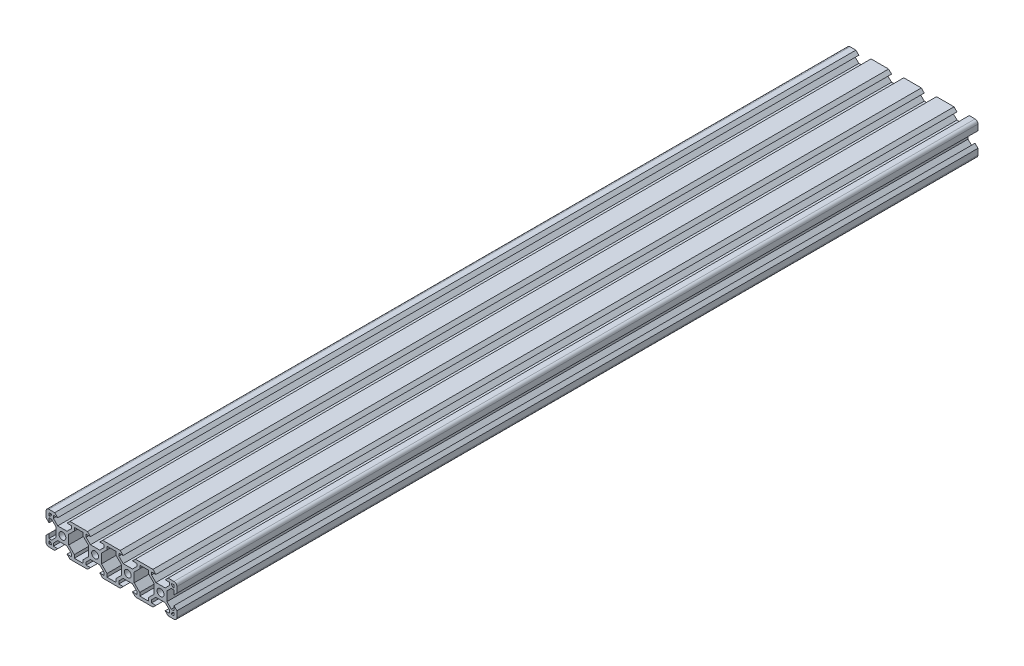
SolidWorks part; units mm, degrees
material "6063-T5"
ref_plane "Plane1" through (0, 0, 0) normal (0, 0, 1) x (1, 0, 0)
ref_plane "Plane2" through (0, 0, 0) normal (0, 1, 0) x (1, 0, 0)
ref_plane "Plane3" through (0, 0, 0) normal (1, 0, 0) x (0, 0, -1)
sketch "Sketch1" plane through (0, 0, 0) normal (0, 0, 1) x (1, 0, 0)
  line L0 (0, 0) -> (0, 10) construction
  line L1 (0, 0) -> (-40, 0) construction
  line L2 (-40, 10) -> (-30, 0) construction
  line L3 (-30, 0) -> (-20, 10) construction
  line L4 (-20, 10) -> (-10, 0) construction
  line L5 (-10, 0) -> (0, 10) construction
  line L6 (-10, 0) -> (-10, 10) construction
  line L7 (-20, 10) -> (-20, 0) construction
  line L8 (-40, 0) -> (-40, 10) construction
  line L9 (-38.2, 10) -> (-34.64, 10)
  line L10 (-34.64, 10) -> (-32.84, 8.2)
  line L11 (-32.84, 8.2) -> (-35.4993, 8.2)
  line L12 (-35.4993, 8.2) -> (-35.4993, 6.56)
  line L13 (-35.4993, 6.56) -> (-32.84, 3.9007)
  line L14 (-32.84, 3.9007) -> (-27.16, 3.9007)
  line L15 (-30, 0) -> (-30, 10) construction
  line L16 (-33.9007, 2.84) -> (-33.9007, 0)
  line L17 (-36.56, 5.4993) -> (-33.9007, 2.84)
  line L18 (-38.2, 5.4993) -> (-36.56, 5.4993)
  line L19 (-38.2, 2.84) -> (-38.2, 5.4993)
  line L20 (-40, 4.64) -> (-38.2, 2.84)
  line L21 (-40, 8.2) -> (-40, 4.64)
  line L22 (-38.2, 8.2) -> (-38.2, 6.5693)
  line L23 (-38.2, 6.5693) -> (-37.63, 6.5693)
  line L24 (-37.63, 6.5693) -> (-36.5693, 7.63)
  line L25 (-36.5693, 7.63) -> (-36.5693, 8.2)
  line L26 (-36.5693, 8.2) -> (-38.2, 8.2)
  line L27 (-17.3, 6.2393) -> (-17.3, 8.2)
  line L28 (-13.9007, 2.84) -> (-17.3, 6.2393)
  line L29 (-13.9007, -2.84) -> (-13.9007, 2.84)
  line L30 (-14.64, 10) -> (-12.84, 8.2)
  line L31 (-12.84, 8.2) -> (-15.4993, 8.2)
  line L32 (-15.4993, 8.2) -> (-15.4993, 6.56)
  line L33 (-15.4993, 6.56) -> (-12.84, 3.9007)
  line L34 (-12.84, 3.9007) -> (-7.16, 3.9007)
  line L35 (-5.36, 10) -> (-7.16, 8.2)
  line L36 (-7.16, 8.2) -> (-4.5007, 8.2)
  line L37 (-4.5007, 8.2) -> (-4.5007, 6.56)
  line L38 (-4.5007, 6.56) -> (-7.16, 3.9007)
  line L39 (-5.36, 10) -> (5.36, 10)
  line L40 (-6.0993, -2.84) -> (-6.0993, 2.84)
  line L41 (-6.0993, 2.84) -> (-2.7, 6.2393)
  line L42 (-2.7, 6.2393) -> (-2.7, 8.2)
  line L43 (-2.7, 8.2) -> (2.7, 8.2)
  line L44 (-25.36, 10) -> (-27.16, 8.2)
  line L45 (-7.16, 3.9007) -> (-6.0993, 2.84) construction
  line L46 (-36.5693, -7.63) -> (-36.5693, -8.2)
  line L47 (-37.63, -6.5693) -> (-36.5693, -7.63)
  line L48 (-38.2, -6.5693) -> (-37.63, -6.5693)
  line L49 (-38.2, -8.2) -> (-38.2, -6.5693)
  line L50 (-27.16, 8.2) -> (-24.5007, 8.2)
  line L51 (-24.5007, 8.2) -> (-24.5007, 6.56)
  line L52 (-24.5007, 6.56) -> (-27.16, 3.9007)
  line L53 (-25.36, 10) -> (-14.64, 10)
  line L54 (-26.0993, -2.84) -> (-26.0993, 2.84)
  line L55 (-26.0993, 2.84) -> (-22.7, 6.2393)
  line L56 (-22.7, 6.2393) -> (-22.7, 8.2)
  line L57 (-22.7, 8.2) -> (-17.3, 8.2)
  line L58 (-27.16, 3.9007) -> (-26.0993, 2.84) construction
  line L59 (-26.0993, 2.84) -> (-26.0962, 2.8177) construction
  line L60 (-36.5693, -8.2) -> (-38.2, -8.2)
  line L61 (-26.0993, -2.84) -> (-22.7, -6.2393)
  line L62 (-22.7, -6.2393) -> (-22.7, -8.2)
  line L63 (-22.7, -8.2) -> (-17.3, -8.2)
  line L64 (-17.3, -6.2393) -> (-17.3, -8.2)
  line L65 (-13.9007, -2.84) -> (-17.3, -6.2393)
  line L66 (-2.7, -8.2) -> (2.7, -8.2)
  line L67 (-2.7, -6.2393) -> (-2.7, -8.2)
  line L68 (-6.0993, -2.84) -> (-2.7, -6.2393)
  line L69 (-5.36, -10) -> (5.36, -10)
  line L70 (-5.36, -10) -> (-7.16, -8.2)
  line L71 (-7.16, -8.2) -> (-4.5007, -8.2)
  line L72 (-4.5007, -8.2) -> (-4.5007, -6.56)
  line L73 (-4.5007, -6.56) -> (-7.16, -3.9007)
  line L74 (-12.84, -3.9007) -> (-7.16, -3.9007)
  line L75 (-15.4993, -6.56) -> (-12.84, -3.9007)
  line L76 (-15.4993, -8.2) -> (-15.4993, -6.56)
  line L77 (-12.84, -8.2) -> (-15.4993, -8.2)
  line L78 (-14.64, -10) -> (-12.84, -8.2)
  line L79 (-25.36, -10) -> (-14.64, -10)
  line L80 (-25.36, -10) -> (-27.16, -8.2)
  line L81 (-27.16, -8.2) -> (-24.5007, -8.2)
  line L82 (-24.5007, -8.2) -> (-24.5007, -6.56)
  line L83 (-24.5007, -6.56) -> (-27.16, -3.9007)
  line L84 (-32.84, -3.9007) -> (-27.16, -3.9007)
  line L85 (-35.4993, -6.56) -> (-32.84, -3.9007)
  line L86 (-35.4993, -8.2) -> (-35.4993, -6.56)
  line L87 (-32.84, -8.2) -> (-35.4993, -8.2)
  line L88 (-34.64, -10) -> (-32.84, -8.2)
  line L89 (-38.2, -10) -> (-34.64, -10)
  line L90 (-40, -8.2) -> (-40, -4.64)
  line L91 (-40, -4.64) -> (-38.2, -2.84)
  line L92 (-38.2, -2.84) -> (-38.2, -5.4993)
  line L93 (-38.2, -5.4993) -> (-36.56, -5.4993)
  line L94 (-36.56, -5.4993) -> (-33.9007, -2.84)
  line L95 (-33.9007, -2.84) -> (-33.9007, 0)
  line L96 (36.5693, 8.2) -> (38.2, 8.2)
  line L97 (36.5693, 7.63) -> (36.5693, 8.2)
  line L98 (37.63, 6.5693) -> (36.5693, 7.63)
  line L99 (38.2, 6.5693) -> (37.63, 6.5693)
  line L100 (38.2, 8.2) -> (38.2, 6.5693)
  line L101 (36.5693, -8.2) -> (38.2, -8.2)
  line L102 (36.5693, -7.63) -> (36.5693, -8.2)
  line L103 (37.63, -6.5693) -> (36.5693, -7.63)
  line L104 (38.2, -6.5693) -> (37.63, -6.5693)
  line L105 (38.2, -8.2) -> (38.2, -6.5693)
  line L106 (13.9007, -2.84) -> (17.3, -6.2393)
  line L107 (17.3, -6.2393) -> (17.3, -8.2)
  line L108 (22.7, -8.2) -> (17.3, -8.2)
  line L109 (22.7, -6.2393) -> (22.7, -8.2)
  line L110 (26.0993, -2.84) -> (22.7, -6.2393)
  line L111 (26.0993, -2.84) -> (26.0993, 2.84)
  line L112 (26.0993, 2.84) -> (22.7, 6.2393)
  line L113 (22.7, 6.2393) -> (22.7, 8.2)
  line L114 (22.7, 8.2) -> (17.3, 8.2)
  line L115 (17.3, 6.2393) -> (17.3, 8.2)
  line L116 (13.9007, 2.84) -> (17.3, 6.2393)
  line L117 (13.9007, -2.84) -> (13.9007, 2.84)
  line L118 (2.7, -6.2393) -> (2.7, -8.2)
  line L119 (6.0993, -2.84) -> (2.7, -6.2393)
  line L120 (6.0993, -2.84) -> (6.0993, 2.84)
  line L121 (6.0993, 2.84) -> (2.7, 6.2393)
  line L122 (2.7, 6.2393) -> (2.7, 8.2)
  line L123 (5.36, -10) -> (7.16, -8.2)
  line L124 (7.16, -8.2) -> (4.5007, -8.2)
  line L125 (4.5007, -8.2) -> (4.5007, -6.56)
  line L126 (4.5007, -6.56) -> (7.16, -3.9007)
  line L127 (12.84, -3.9007) -> (7.16, -3.9007)
  line L128 (15.4993, -6.56) -> (12.84, -3.9007)
  line L129 (15.4993, -8.2) -> (15.4993, -6.56)
  line L130 (12.84, -8.2) -> (15.4993, -8.2)
  line L131 (14.64, -10) -> (12.84, -8.2)
  line L132 (25.36, -10) -> (14.64, -10)
  line L133 (25.36, -10) -> (27.16, -8.2)
  line L134 (27.16, -8.2) -> (24.5007, -8.2)
  line L135 (24.5007, -8.2) -> (24.5007, -6.56)
  line L136 (24.5007, -6.56) -> (27.16, -3.9007)
  line L137 (32.84, -3.9007) -> (27.16, -3.9007)
  line L138 (35.4993, -6.56) -> (32.84, -3.9007)
  line L139 (35.4993, -8.2) -> (35.4993, -6.56)
  line L140 (32.84, -8.2) -> (35.4993, -8.2)
  line L141 (34.64, -10) -> (32.84, -8.2)
  line L142 (38.2, -10) -> (34.64, -10)
  line L143 (40, -8.2) -> (40, -4.64)
  line L144 (40, -4.64) -> (38.2, -2.84)
  line L145 (38.2, -2.84) -> (38.2, -5.4993)
  line L146 (38.2, -5.4993) -> (36.56, -5.4993)
  line L147 (36.56, -5.4993) -> (33.9007, -2.84)
  line L148 (33.9007, -2.84) -> (33.9007, 0)
  line L149 (33.9007, 2.84) -> (33.9007, 0)
  line L150 (36.56, 5.4993) -> (33.9007, 2.84)
  line L151 (38.2, 5.4993) -> (36.56, 5.4993)
  line L152 (38.2, 2.84) -> (38.2, 5.4993)
  line L153 (40, 4.64) -> (38.2, 2.84)
  line L154 (40, 8.2) -> (40, 4.64)
  line L155 (38.2, 10) -> (34.64, 10)
  line L156 (34.64, 10) -> (32.84, 8.2)
  line L157 (32.84, 8.2) -> (35.4993, 8.2)
  line L158 (35.4993, 8.2) -> (35.4993, 6.56)
  line L159 (35.4993, 6.56) -> (32.84, 3.9007)
  line L160 (32.84, 3.9007) -> (27.16, 3.9007)
  line L161 (24.5007, 6.56) -> (27.16, 3.9007)
  line L162 (24.5007, 8.2) -> (24.5007, 6.56)
  line L163 (27.16, 8.2) -> (24.5007, 8.2)
  line L164 (25.36, 10) -> (27.16, 8.2)
  line L165 (25.36, 10) -> (14.64, 10)
  line L166 (14.64, 10) -> (12.84, 8.2)
  line L167 (12.84, 8.2) -> (15.4993, 8.2)
  line L168 (15.4993, 8.2) -> (15.4993, 6.56)
  line L169 (15.4993, 6.56) -> (12.84, 3.9007)
  line L170 (12.84, 3.9007) -> (7.16, 3.9007)
  line L171 (4.5007, 6.56) -> (7.16, 3.9007)
  line L172 (4.5007, 8.2) -> (4.5007, 6.56)
  line L173 (7.16, 8.2) -> (4.5007, 8.2)
  line L174 (5.36, 10) -> (7.16, 8.2)
  circle A0 centre (-30, 0) radius 2.1
  circle A1 centre (-10, 0) radius 2.1
  arc A2 (-38.2, 10) -> (-40, 8.2) centre (-38.2, 8.2) ccw
  arc A3 (-38.2, -10) -> (-40, -8.2) centre (-38.2, -8.2) cw
  circle A4 centre (30, 0) radius 2.1
  circle A5 centre (10, 0) radius 2.1
  arc A6 (38.2, -10) -> (40, -8.2) centre (38.2, -8.2) ccw
  arc A7 (38.2, 10) -> (40, 8.2) centre (38.2, 8.2) cw
  point P21 (-37.0997, 7.0997)
  point P36 (-20, 8.2)
  point P47 (-10, 3.9007)
  point P54 (-6.6297, 3.3703)
  point P61 (-30, 3.9007)
  point P71 (-26.0993, 0)
  point P76 (-13.9007, 0)
  point P80 (-6.0993, 0)
  point P135 (0, -8.2)
  point P140 (0, 8.2)
  point P141 (0, -10)
  dimension "D3" = 4.2
  dimension "D4" = 4.2
  dimension "D1" = 40
  dimension "D2" = 10
  dimension "D5" = 5.68
  dimension "D6" = 1.5
  dimension "D7" = 1.64
  dimension "D8" = 1.8
  dimension "D9" = 1.07
  dimension "D11" = 5.4
extrude "Extrude1" add sketch "Sketch1" along normal mid plane 489.6
